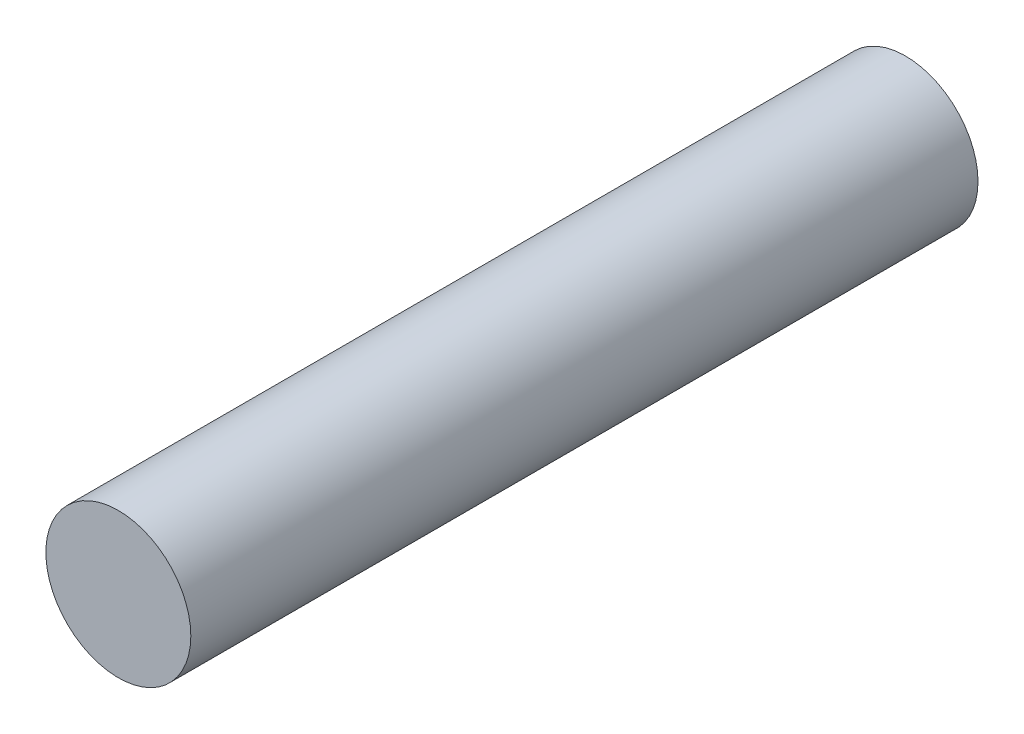
SolidWorks part; units mm, degrees
ref_plane "Front Plane" through (0, 0, 0) normal (0, 0, 1) x (1, 0, 0)
ref_plane "Top Plane" through (0, 0, 0) normal (0, 1, 0) x (1, 0, 0)
ref_plane "Right Plane" through (0, 0, 0) normal (1, 0, 0) x (0, 0, -1)
sketch "Sketch1" plane through (0, 0, 0) normal (0, 0, 1) x (1, 0, 0)
  circle A0 centre (0, 0) radius 12.7
  dimension "D1" = 25.4
extrude "Boss-Extrude1" add sketch "Sketch1" along normal blind 137.922
